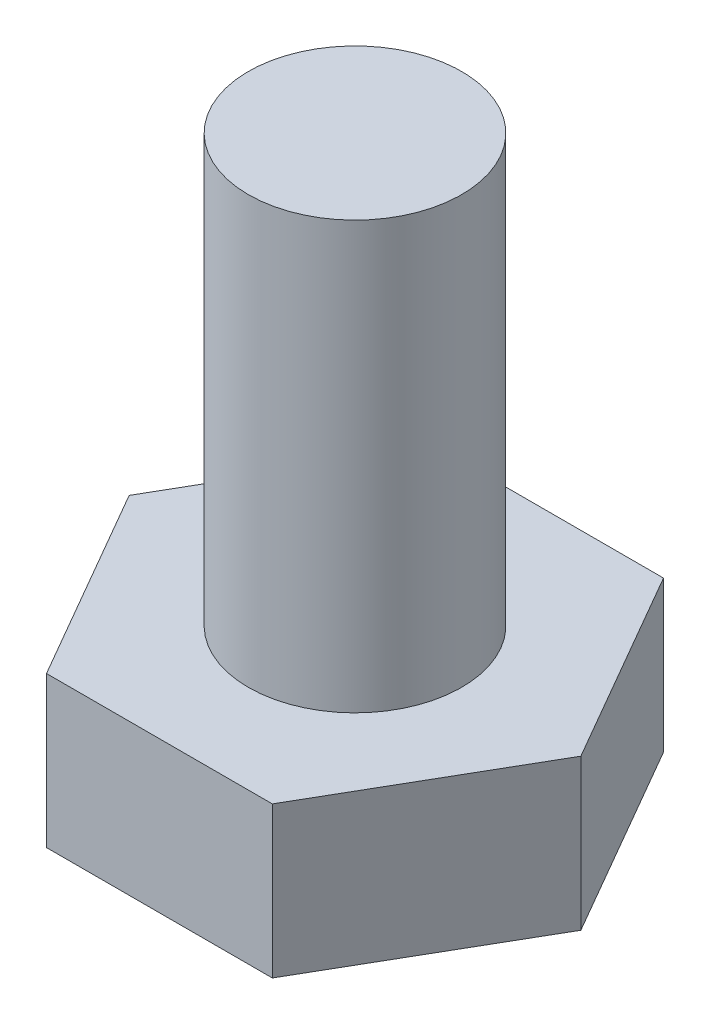
SolidWorks part; units mm, degrees
ref_plane "前视基准面" through (0, 0, 0) normal (0, 0, 1) x (1, 0, 0)
ref_plane "上视基准面" through (0, 0, 0) normal (0, 1, 0) x (1, 0, 0)
ref_plane "右视基准面" through (0, 0, 0) normal (1, 0, 0) x (0, 0, -1)
sketch "草图1" plane through (0, 0, 0) normal (0, 1, 0) x (1, 0, 0)
  circle A0 centre (0, 0) radius 1.5
  dimension "D1" = 3
extrude "凸台-拉伸1" add sketch "草图1" along normal blind 6
sketch "草图3" plane through (0, 0, 0) normal (0, -1, 0) x (1, 0, 0)
  line L1 (3.1754, 0) -> (1.5877, 2.75)
  line L2 (1.5877, 2.75) -> (-1.5877, 2.75)
  line L3 (-1.5877, 2.75) -> (-3.1754, 0)
  line L4 (-3.1754, 0) -> (-1.5877, -2.75)
  line L5 (-1.5877, -2.75) -> (1.5877, -2.75)
  line L6 (1.5877, -2.75) -> (3.1754, 0)
  circle A0 centre (0, 0) radius 2.75 construction
  dimension "D1" = 5.5
extrude "凸台-拉伸2" add sketch "草图3" along normal blind 2.12 contours L5 L6 L1 L2 L3 L4
